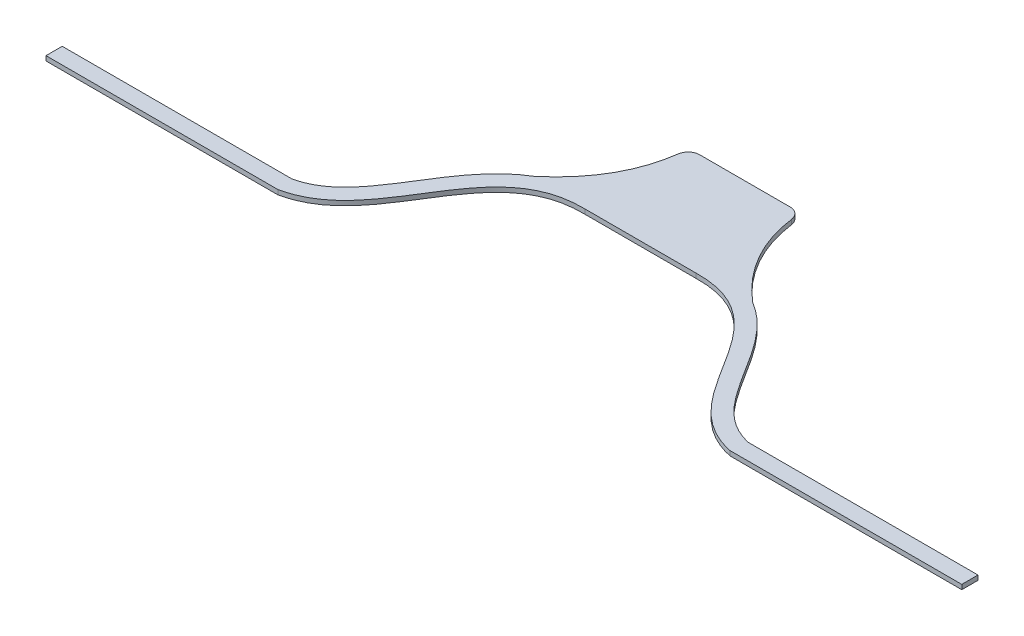
SolidWorks part; units mm, degrees
ref_plane "Front Plane" through (0, 0, 0) normal (0, 0, 1) x (1, 0, 0)
ref_plane "Top Plane" through (0, 0, 0) normal (0, 1, 0) x (1, 0, 0)
ref_plane "Right Plane" through (0, 0, 0) normal (1, 0, 0) x (0, 0, -1)
sketch "Sketch1" plane through (0, 0, 0) normal (0, 1, 0) x (1, 0, 0)
  line L0 (24, 0) -> (24, 62.3961) construction
  line L1 (24, 0) -> (48, 0)
  line L2 (24, 45) -> (24, 0)
  line L3 (24, 45) -> (43.488, 45)
  line L4 (221.5478, -51.9864) -> (221.5478, -58.9864)
  line L5 (121.5478, -58.9864) -> (221.5478, -58.9864)
  line L6 (122.313, -51.9864) -> (221.5478, -51.9864)
  arc A0 (43.488, 45) -> (48.4437, 40.6644) centre (43.488, 40) cw
  spline S0 degree 3 poles (48, 0) (89.0994, 0.8748) (86.3741, -51.6031) (121.5478, -58.9864) knots 0 0 0 0 1 1 1 1
  spline S1 degree 1 poles (47.851, 6.9984) (122.313, -51.9864) knots 0 0 1 1 construction
  spline S2 degree 3 poles (47.851, 6.9984) (48.5715, 7.0137) (50.0255, 7.0159) (52.8331, 6.9038) (56.226, 6.5497) (60.0876, 5.7925) (64.9572, 4.3617) (70.4978, 1.8366) (76.2516, -2.1215) (81.1897, -6.7263) (86.8914, -13.4164) (92.8078, -22.3476) (98.1299, -31.0609) (102.4697, -37.3452) (105.8428, -41.5805) (109.401, -45.225) (112.5772, -47.7109) (115.3062, -49.3584) (117.4705, -50.4224) (119.3998, -51.1642) (121.0274, -51.6649) (121.8858, -51.8864) (122.313, -51.9864) knots 0 0 0 0 0.015501 0.031002 0.062004 0.093006 0.124008 0.186013 0.248017 0.310021 0.372025 0.496034 0.620042 0.682046 0.74405 0.806054 0.868059 0.899061 0.930063 0.961065 0.976566 0.992067 0.992067 0.992067 0.992067 only from (71.126, 1.2325) to (122.313, -51.9864)
  spline S3 degree 3 poles (48.4437, 40.6644) (50.6204, 24.4295) (58.9818, 11.4483) (71.126, 1.2325) knots 0.080376 0.080376 0.080376 0.080376 1 1 1 1
  dimension "D1" = 5
  dimension "D3" = 100
  dimension "D4" = 7
extrude "Boss-Extrude1" add sketch "Sketch1" along normal blind 2
mirror "Mirror1" about plane through (24, 2, -45) normal (1, 0, 0) of "Boss-Extrude1"
